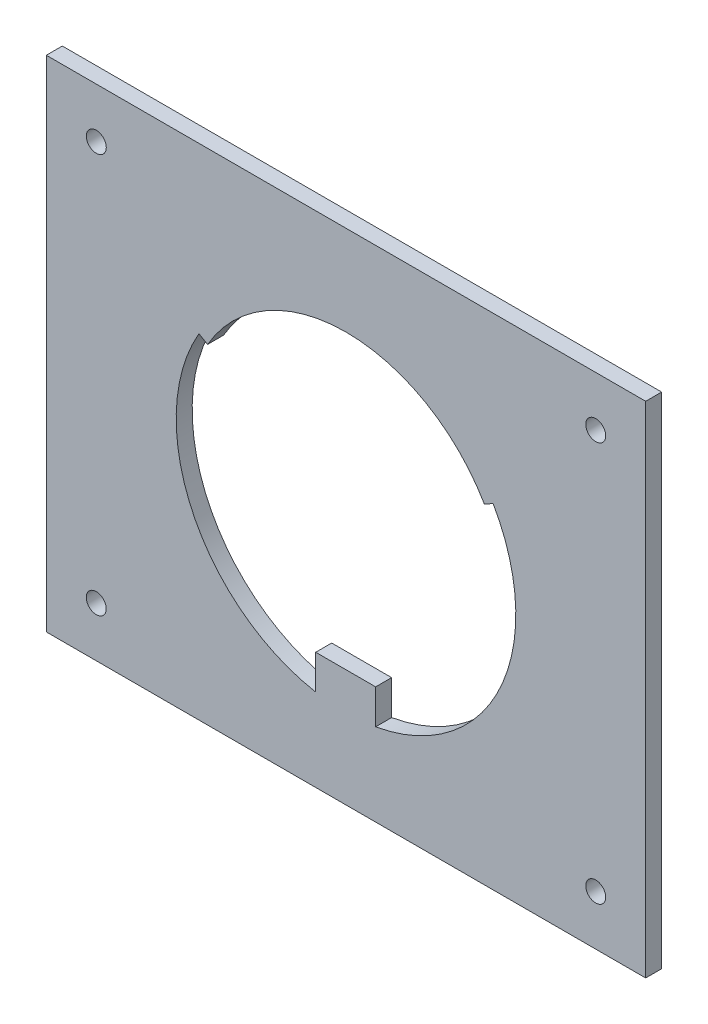
SolidWorks part; units mm, degrees
ref_plane "Front Plane" through (0, 0, 0) normal (0, 0, 1) x (1, 0, 0)
ref_plane "Top Plane" through (0, 0, 0) normal (0, 1, 0) x (1, 0, 0)
ref_plane "Right Plane" through (0, 0, 0) normal (1, 0, 0) x (0, 0, -1)
sketch "Sketch1" plane through (0, 0, 0) normal (0, 0, 1) x (1, 0, 0)
  line L0 (-0.8496, -12.7268) -> (5.1504, -12.7268)
  line L1 (-0.8496, -12.7268) -> (-0.8496, -16.179)
  line L2 (5.1504, -12.7268) -> (5.1504, -16.191)
  line L3 (-11.6728, 8.5482) -> (-12.5388, 9.0482)
  line L4 (16.906, 9.0482) -> (16.04, 8.5482)
  line L5 (2.1836, -24.4518) -> (2.1836, 25.5482) construction
  line L6 (-27.8164, 25.5482) -> (32.1836, 25.5482)
  line L7 (-27.8164, 25.5482) -> (-27.8164, -24.4518)
  line L8 (-27.8164, -24.4518) -> (32.1836, -24.4518)
  line L9 (32.1836, 25.5482) -> (32.1836, -24.4518)
  line L10 (-27.8164, 25.5482) -> (32.1836, -24.4518) construction
  line L11 (-27.8164, -24.4518) -> (32.1836, 25.5482) construction
  line L12 (32.1836, 0.5482) -> (-27.8164, 0.5482) construction
  arc A0 (16.04, 8.5482) -> (-11.6728, 8.5482) centre (2.1836, 0.5482) ccw
  arc A1 (-12.5388, 9.0482) -> (-0.8496, -16.179) centre (2.1836, 0.5482) ccw
  arc A2 (5.1504, -16.191) -> (16.906, 9.0482) centre (2.1836, 0.5482) ccw
  circle A3 centre (-22.8164, 20.5482) radius 1
  circle A4 centre (27.1836, 20.5482) radius 1
  circle A5 centre (27.1836, -19.4518) radius 1
  circle A6 centre (-22.8164, -19.4518) radius 1
  point P2 (2.1504, -12.7268)
  dimension "D3" = 17
  dimension "D4" = 16
  dimension "D5" = 2
  dimension "D6" = 5
  dimension "D7" = 5
  dimension "D1" = 60
  dimension "D2" = 50
extrude "Boss-Extrude1" add sketch "Sketch1" along normal blind 1.6
